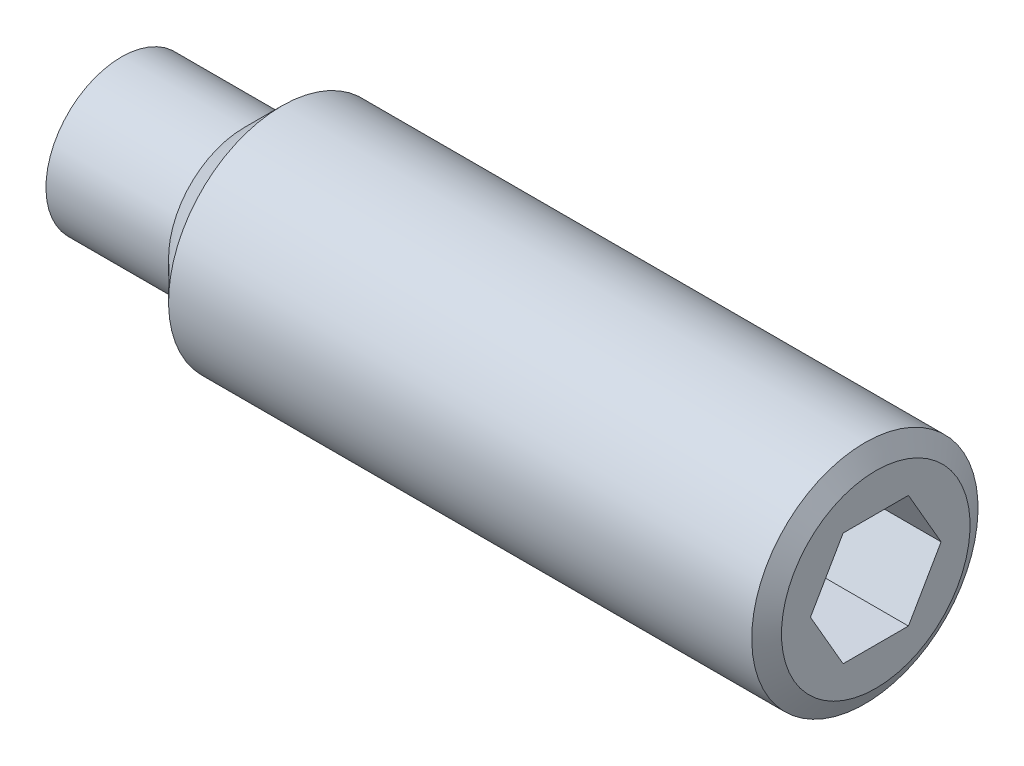
SolidWorks part; units mm, degrees
material "AISI 1020"
ref_plane "Front Plane" through (0, 0, 0) normal (0, 0, 1) x (1, 0, 0)
ref_plane "Top Plane" through (0, 0, 0) normal (0, 1, 0) x (1, 0, 0)
ref_plane "Right Plane" through (0, 0, 0) normal (1, 0, 0) x (0, 0, -1)
sketch "Sketch1" plane through (0, 0, 0) normal (0, 0, 1) x (1, 0, 0)
  line L0 (0, 0) -> (-20, 0) construction
  line L1 (0, 0) -> (0, 3)
  line L2 (0, 3) -> (-15.75, 3)
  line L3 (-15.75, 3) -> (-16.75, 2)
  line L4 (-16.75, 2) -> (-20, 2)
  line L5 (-20, 2) -> (-20, 0)
  line L6 (-20, 0) -> (0, 0)
  dimension "Dog diam" = 4
  dimension "Diam" = 6
  dimension "D3" = 45
  dimension "Dog ilgis" = 3.25
  dimension "Ilgis" = 20
revolve "Revolve1" add sketch "Sketch1" angle 360 about L0
cosmetic thread "Cosmetic Thread1" parameters "Sr_diam"=5
sketch "Sketch2" plane through (0, 0, 0) normal (1, 0, 0) x (0, 0, -1)
  line L1 (1.7321, 0) -> (0.866, 1.5)
  line L2 (0.866, 1.5) -> (-0.866, 1.5)
  line L3 (-0.866, 1.5) -> (-1.7321, 0)
  line L4 (-1.7321, 0) -> (-0.866, -1.5)
  line L5 (-0.866, -1.5) -> (0.866, -1.5)
  line L6 (0.866, -1.5) -> (1.7321, 0)
  circle A0 centre (0, 0) radius 1.5 construction
  dimension "R_dydis" = 3
extrude "Cut-Extrude1" cut sketch "Sketch2" against normal blind 3.5
chamfer "Chamfer1" distance 0.5 angle 30 1 edges at (0, 3, 0)
